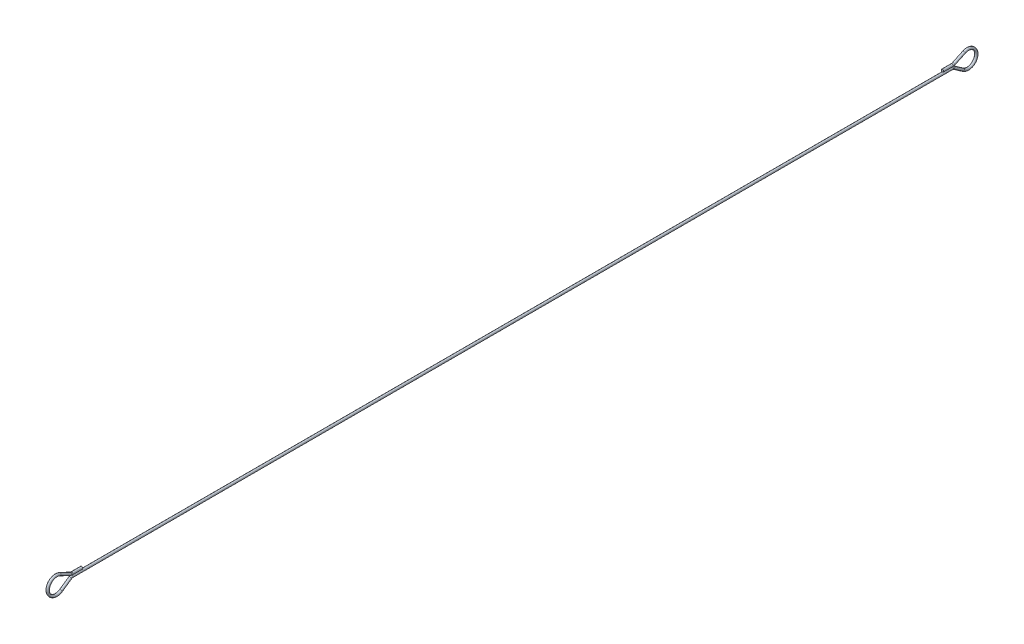
SolidWorks part; units mm, degrees
material "Plain Carbon Steel"
ref_plane "Front Plane" through (0, 0, 0) normal (0, 0, 1) x (1, 0, 0)
ref_plane "Top Plane" through (0, 0, 0) normal (0, 1, 0) x (1, 0, 0)
ref_plane "Right Plane" through (0, 0, 0) normal (1, 0, 0) x (0, 0, -1)
sketch "Sketch1" plane through (0, 0, 0) normal (1, 0, 0) x (0, 0, -1)
  line L0 (0, 0) -> (-577.8891, 0)
  line L1 (-579.7008, -0.5676) -> (-592.0896, -9.1759)
  line L2 (-593.7068, 10.1096) -> (-580.0574, 3.6848)
  line L3 (-577.8891, 3.2) -> (-565.1891, 3.2)
  line L4 (-577.8891, 3.2) -> (-577.8891, 0) construction
  line L5 (55, 0) -> (-55, 0) construction
  arc A0 (-577.8891, 0) -> (-579.7008, -0.5676) centre (-577.8891, -3.175) ccw
  arc A1 (-592.0896, -9.1759) -> (-593.7068, 10.1096) centre (-598.4655, 0) cw
  arc A2 (-580.0574, 3.6848) -> (-577.8891, 3.2) centre (-577.8891, 8.2913) ccw
  point P16 (-609.6, -0.9337)
  dimension "D3" = 3.175
  dimension "D1" = 3.2
  dimension "D2" = 12.7
  dimension "D4" = 31.75
  dimension "D5" = 60
  dimension "D6" = 609.6
sketch "Sketch2" plane through (0, 0, 0) normal (0, 0, 1) x (1, 0, 0)
  line L0 (0, -11.1736) -> (0, 11.1736) construction
  circle A0 centre (0, 0) radius 1.5875
  dimension "D1" = 3.175
sweep "Sweep1" add profiles "Sketch2" path "Sketch1"
mirror "Mirror1" about plane through (0, 0, 0) normal (0, 0, 1) of "Sweep1"
